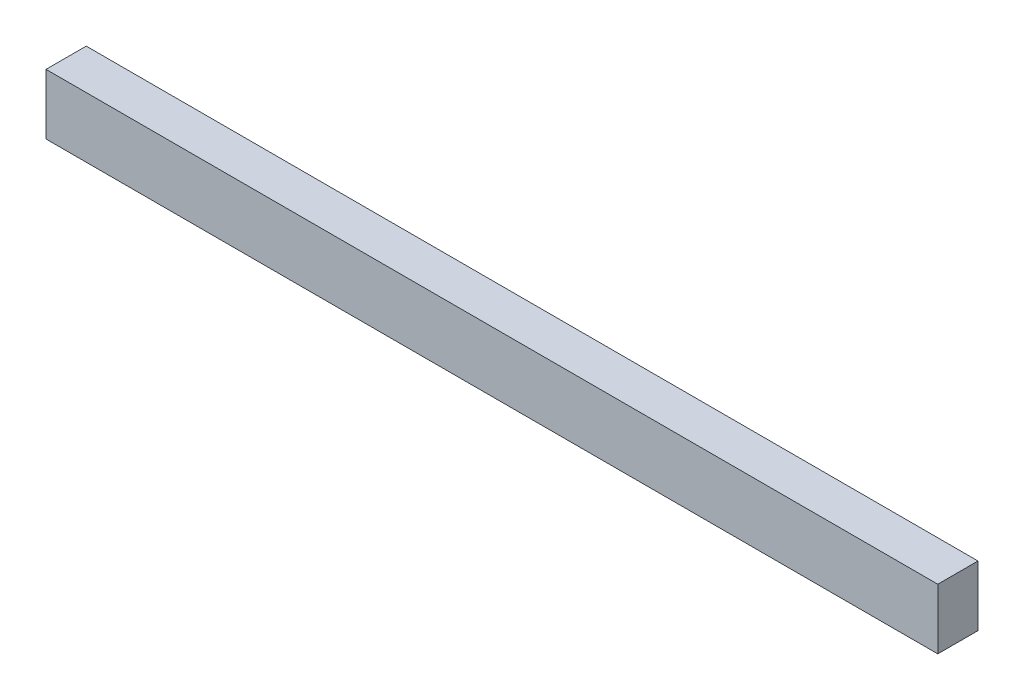
SolidWorks part; units mm, degrees
ref_plane "Front Plane" through (0, 0, 0) normal (0, 0, 1) x (1, 0, 0)
ref_plane "Top Plane" through (0, 0, 0) normal (0, 1, 0) x (1, 0, 0)
ref_plane "Right Plane" through (0, 0, 0) normal (1, 0, 0) x (0, 0, -1)
sketch "Sketch1" plane through (0, 0, 0) normal (0, 1, 0) x (1, 0, 0)
  line L1 (-168.3194, 67.9761) -> (230.6806, 67.9761)
  line L2 (-168.3194, 67.9761) -> (-168.3194, 49.9761)
  line L3 (-168.3194, 49.9761) -> (230.6806, 49.9761)
  line L4 (230.6806, 67.9761) -> (230.6806, 49.9761)
  line L5 (-168.3194, 67.9761) -> (230.6806, 49.9761) construction
  line L6 (-168.3194, 49.9761) -> (230.6806, 67.9761) construction
  point P4 (31.1806, 58.9761)
  dimension "D1" = 399
  dimension "D2" = 18
extrude "Boss-Extrude1" add sketch "Sketch1" along normal blind 27
